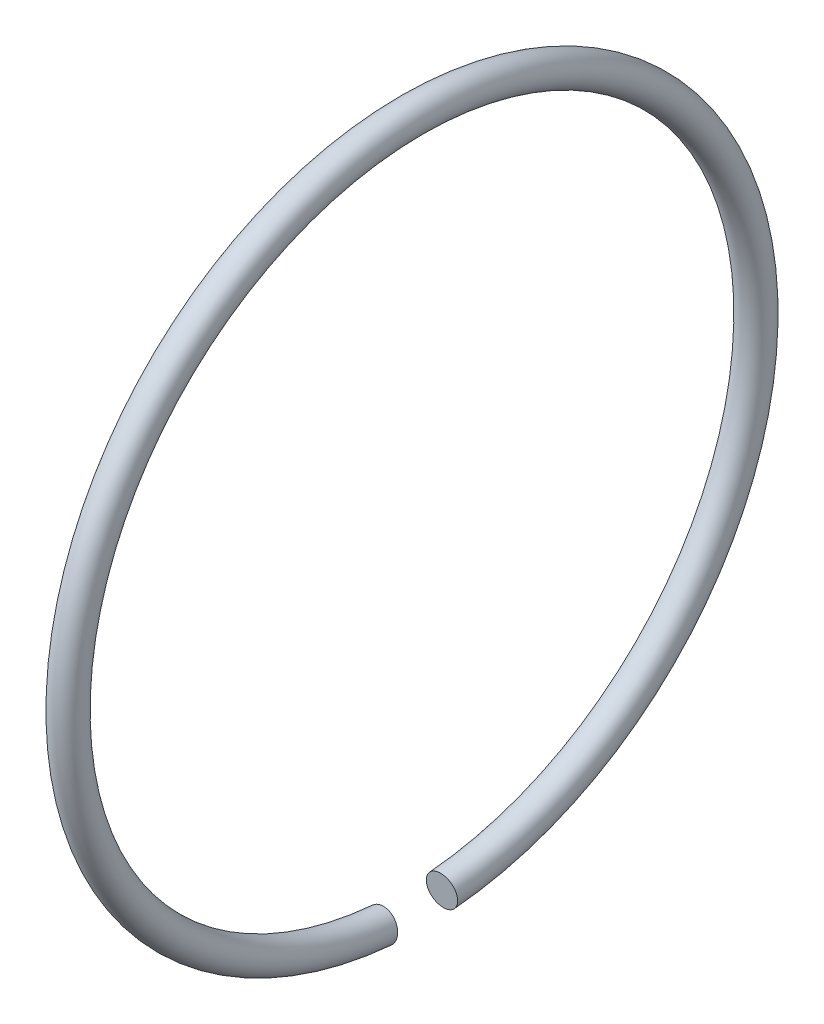
SolidWorks part; units mm, degrees
ref_plane "Front Plane" through (0, 0, 0) normal (0, 0, 1) x (1, 0, 0)
ref_plane "Top Plane" through (0, 0, 0) normal (0, 1, 0) x (1, 0, 0)
ref_plane "Right Plane" through (0, 0, 0) normal (1, 0, 0) x (0, 0, -1)
ref_plane "Plane1" through (0, 0, 0) normal (0, 0, 1) x (1, 0, 0)
sketch "Sketch1" plane through (0, 0, 0) normal (0, 0, 1) x (1, 0, 0)
  line L0 (0.5, 0) -> (-0.5, 0) construction
  circle A0 centre (0, 11) radius 0.5
revolve "Revolve1" add sketch "Sketch1" angle 175 about L0
